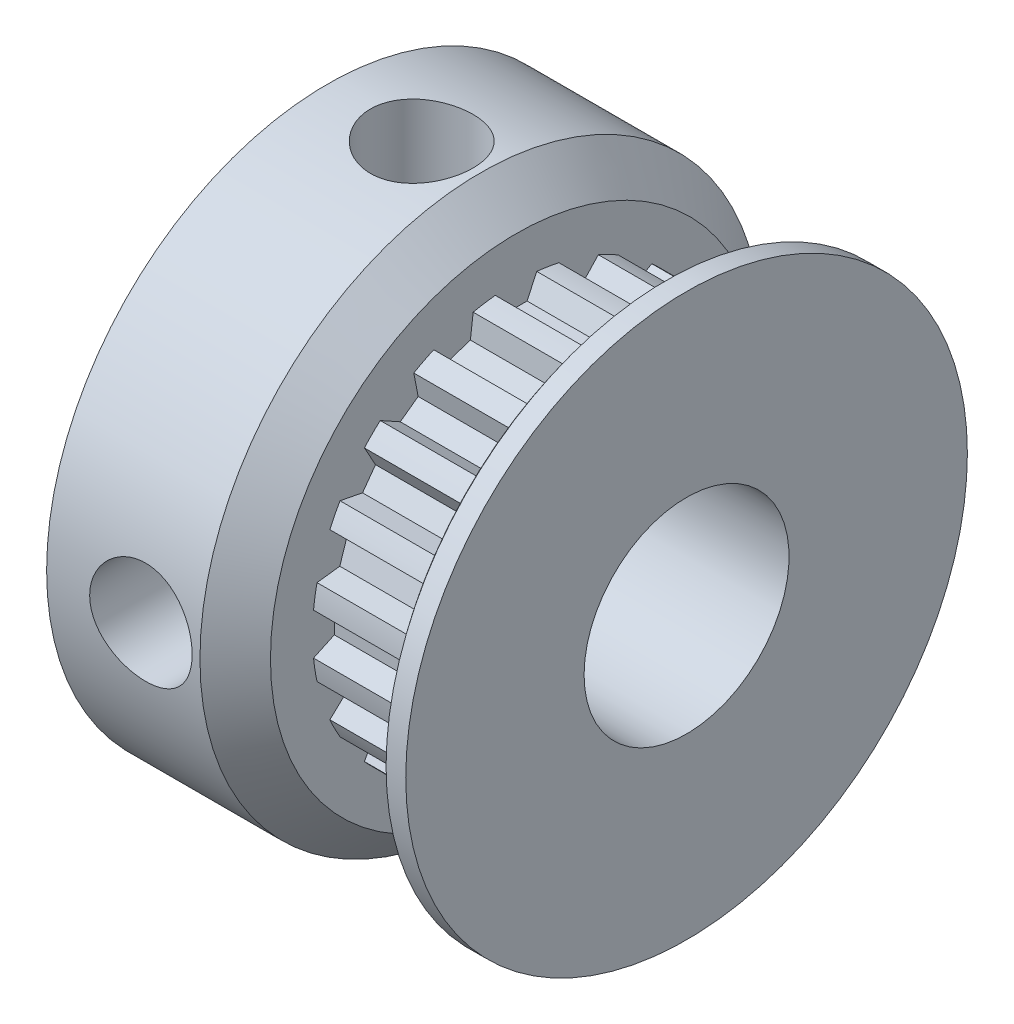
SolidWorks part; units mm, degrees
ref_plane "Front Plane" through (0, 0, 0) normal (0, 0, 1) x (1, 0, 0)
ref_plane "Top Plane" through (0, 0, 0) normal (0, 1, 0) x (1, 0, 0)
ref_plane "Right Plane" through (0, 0, 0) normal (1, 0, 0) x (0, 0, -1)
sketch "Sketch2" plane through (0, 0, 0) normal (1, 0, 0) x (0, 0, -1)
  line L3 (0, 0) -> (0, 5.6388) construction
  line L6 (0, -6.1468) -> (0, -6.4643) construction
  line L7 (-0.5715, 6.1202) -> (-0.3422, 5.6284)
  line L8 (0.5715, 6.1202) -> (0.3422, 5.6284)
  line L9 (-0.5715, 6.1202) -> (-0.6426, 6.2727)
  line L10 (0.5715, 6.1202) -> (0.6426, 6.2727)
  line L12 (-0.3422, 5.6284) -> (0.3422, 5.6284)
  line L14 (0, 6.1468) -> (0, 6.4643) construction
  line L15 (0, 0) -> (0, -1.143) construction
  circle A0 centre (0, 0) radius 6.4643 construction
  circle A1 centre (0, 0) radius 5.6388 construction
  circle A2 centre (0, 0) radius 6.1468 construction
  arc A7 (0.6426, 6.2727) -> (-0.6426, 6.2727) centre (0, 0) ccw
  point P5 (0, 6.3056)
  dimension "D3" = 0.3175
  dimension "D1" = 50
sketch "Sketch1" plane through (0, 0, 0) normal (0, 0, 1) x (1, 0, 0)
  line L0 (-5.5626, 0) -> (5.5626, 0) construction
  line L1 (-5.5626, 3.175) -> (5.5626, 3.175)
  line L2 (-5.5626, 3.175) -> (-5.5626, 8.6995)
  line L3 (-5.5626, 8.6995) -> (-0.8128, 8.6995)
  line L4 (-0.8128, 8.6995) -> (0.2794, 7.6073)
  line L5 (0.2794, 7.6073) -> (0.2794, 6.4643)
  line L6 (0.2794, 6.4643) -> (4.3434, 6.4643)
  line L7 (4.3434, 6.4643) -> (4.3434, 7.0358)
  line L8 (4.3434, 6.4643) -> (5.5626, 6.4643) construction
  line L9 (4.953, 8.6995) -> (5.5626, 8.6995)
  line L10 (5.5626, 8.6995) -> (5.5626, 3.175)
  line L11 (4.953, 6.4643) -> (4.953, 8.6995) construction
  line L12 (-3.1877, 8.6995) -> (-3.1877, 3.175) construction
  arc A0 (4.3434, 7.0358) -> (4.953, 8.6995) centre (6.9185, 7.0358) cw
  dimension "Bore Size" = 6.35
  dimension "Overall Width" = 11.1252
  dimension "Inside Width" = 4.064
  dimension "Outside Width" = 5.2832
  dimension "Hub Dia" = 17.399
  dimension "OD" = 17.399
  dimension "D1" = 45
  dimension "D2" = 12.9286
  dimension "D3" = 1.143
  dimension "D4" = 0.5715
revolve "Revolve1" add sketch "Sketch1" angle 360 mid plane about L0
sketch "Sketch4" plane through (0.2794, 0, 0) normal (1, 0, 0) x (0, 0, -1)
  circle A0 centre (0, 0) radius 6.3056
  circle A1 centre (0, 0) radius 6.4643 construction
  circle A2 centre (0, 0) radius 6.4643
extrude "Cut-Extrude2" cut sketch "Sketch4" along normal up to surface (4.064 mm away) up to face at (4.3434, 0, 6.4643)
sketch "Sketch3" plane through (0.2794, 0, 0) normal (1, 0, 0) x (0, 0, -1)
  line L2 (-0.5715, 6.1202) -> (-0.3422, 5.6284) construction
  line L3 (-0.3422, 5.6284) -> (0.3422, 5.6284) construction
  line L4 (0.5715, 6.1202) -> (0.3422, 5.6284) construction
  line L5 (-0.6426, 6.2727) -> (-0.3422, 5.6284)
  line L6 (-0.3422, 5.6284) -> (0.3422, 5.6284)
  line L7 (0.6426, 6.2727) -> (0.3422, 5.6284)
  arc A1 (0.6426, 6.2727) -> (-0.6426, 6.2727) centre (0, 0) ccw construction
  arc A2 (0.6426, 6.2727) -> (-0.6426, 6.2727) centre (0, 0) ccw
extrude "Cut-Extrude1" cut sketch "Sketch3" along normal up to surface (4.064 mm away) up to face at (4.3434, 0, 7.0358)
pattern_circular "CirPattern1" count 20 over 360 about axis through (0, 0, 0) along (1, 0, 0) of "Cut-Extrude1"
sketch "Sketch5" plane through (0, 0, 0) normal (0, 0, 1) x (1, 0, 0)
  line L1 (4.3434, 7.0358) -> (4.3434, -7.0358) construction
  point P0 (4.3434, 0)
sketch "Sketch6" plane through (0, 0, 0) normal (0, 1, 0) x (1, 0, 0)
  line L0 (-5.5626, 0) -> (-4.2291, 0) construction
  line L1 (-5.5626, 8.6995) -> (-5.5626, -8.6995) construction
  line L2 (0.2794, 0) -> (-1.0541, 0) construction
  line L3 (0.2794, -0.3422) -> (0.2794, 0.3422) construction
  circle A0 centre (-2.6416, 0) radius 1.5875
  dimension "D1" = 3.175
extrude "Cut-Extrude3" cut sketch "Sketch6" along normal through all
pattern_circular "CirPattern2" count 2 over 90 about axis through (-5.5626, 0, 0) along (-1, 0, 0) of "Cut-Extrude3"
equation "\"D3@Sketch2\" = (\"hs@Sketch2\"-\"ht@Sketch2\")/2"
equation "\"D2@Sketch1\" = \"PD@Sketch2\""
equation "\"D3@Sketch1\" = \"hs@Sketch2\""
equation "\"D4@Sketch1\" = \"D3@Sketch1\"/2"
